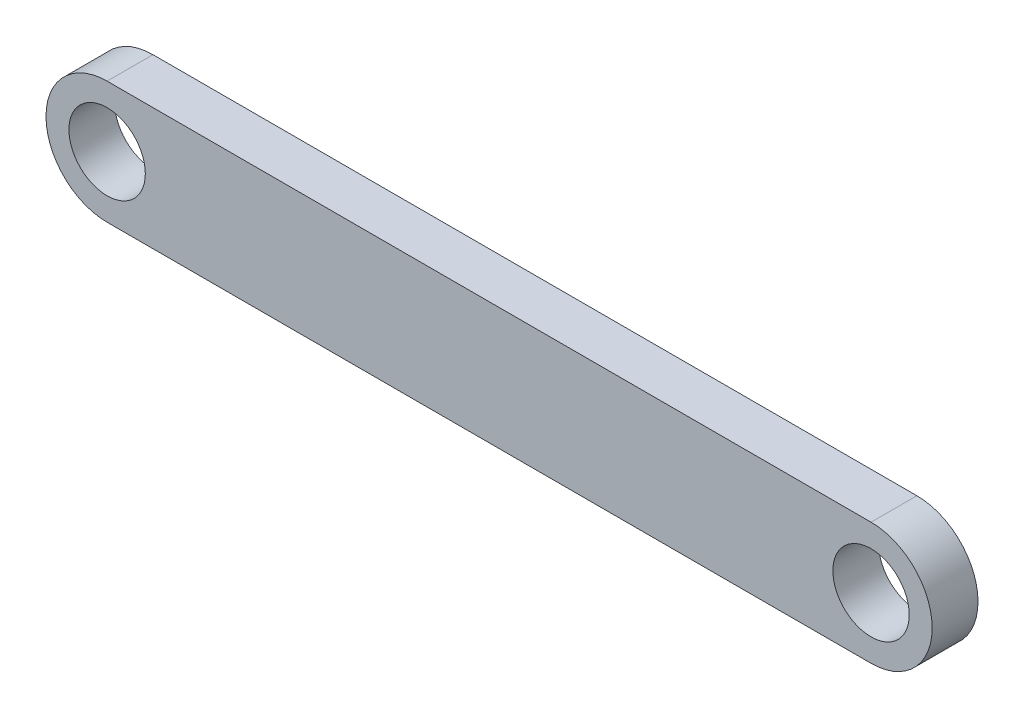
SolidWorks part; units mm, degrees
material "ABS"
ref_plane "Front Plane" through (0, 0, 0) normal (0, 0, 1) x (1, 0, 0)
ref_plane "Top Plane" through (0, 0, 0) normal (0, 1, 0) x (1, 0, 0)
ref_plane "Right Plane" through (0, 0, 0) normal (1, 0, 0) x (0, 0, -1)
sketch "Sketch1" plane through (0, 0, 0) normal (0, 0, 1) x (1, 0, 0)
  line L0 (0, 0) -> (-50, 0)
  dimension "D1" = 50
sketch "Sketch2" plane through (0, 0, 0) normal (0, 0, 1) x (1, 0, 0)
  line L0 (-50, 4) -> (0, 4)
  line L1 (-50, -4) -> (0, -4)
  circle A0 centre (-50, 0) radius 2.5
  circle A1 centre (0, 0) radius 2.5
  arc A2 (-50, 4) -> (-50, -4) centre (-50, 0) ccw
  arc A3 (0, -4) -> (0, 4) centre (0, 0) ccw
  dimension "D1" = 5
  dimension "D2" = 8
  dimension "D3" = 5
  dimension "D4" = 8
extrude "Boss-Extrude1" add sketch "Sketch2" along normal blind 3
